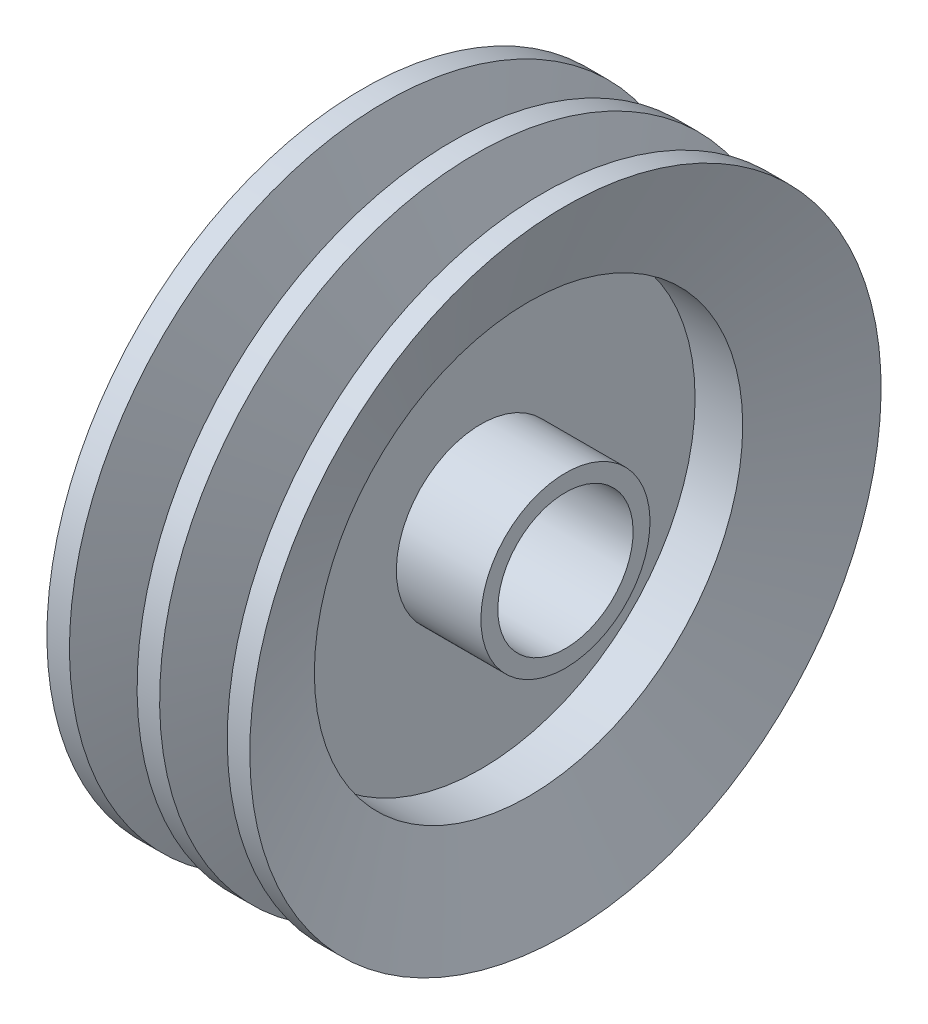
SolidWorks part; units mm, degrees
ref_plane "Alzado" through (0, 0, 0) normal (0, 0, 1) x (1, 0, 0)
ref_plane "Planta" through (0, 0, 0) normal (0, 1, 0) x (1, 0, 0)
ref_plane "Vista lateral" through (0, 0, 0) normal (1, 0, 0) x (0, 0, -1)
sketch "Croquis1" plane through (0, 0, 0) normal (0, 0, 1) x (1, 0, 0)
  line L0 (-45, 0) -> (45, 0) construction
  line L1 (-45, 30) -> (45, 30)
  line L2 (0, 30) -> (0, 140) construction
  line L3 (-5, 140) -> (5, 140)
  line L4 (5, 140) -> (15.9191, 110)
  line L5 (15.9191, 110) -> (24.0809, 110)
  line L6 (24.0809, 110) -> (35, 140)
  line L7 (35, 140) -> (45, 140)
  line L8 (45, 140) -> (28.6213, 95)
  line L9 (28.6213, 95) -> (7.5, 95)
  line L10 (7.5, 95) -> (7.5, 37.5)
  line L11 (7.5, 37.5) -> (45, 37.5)
  line L12 (45, 37.5) -> (45, 30)
  line L13 (-45, 37.5) -> (-45, 30)
  line L14 (-7.5, 37.5) -> (-45, 37.5)
  line L15 (-7.5, 95) -> (-7.5, 37.5)
  line L16 (-28.6213, 95) -> (-7.5, 95)
  line L17 (-45, 140) -> (-28.6213, 95)
  line L18 (-35, 140) -> (-45, 140)
  line L19 (-24.0809, 110) -> (-35, 140)
  line L20 (-15.9191, 110) -> (-24.0809, 110)
  line L21 (-5, 140) -> (-15.9191, 110)
  point P3 (0, 0)
  point P26 (0, 0)
  point P27 (23.5731, 57.0822)
  point P28 (13.471, 110)
  point P29 (31.3763, 95)
  point P30 (14.2787, 110)
  point P31 (0, 0)
  point P32 (0, 0)
  point P33 (0, 0)
  dimension "D1" = 90
  dimension "D2" = 90
  dimension "D3" = 30
  dimension "D4" = 10
  dimension "D5" = 30
  dimension "D6" = 40
  dimension "D7" = 15
  dimension "D8" = 60
  dimension "D9" = 75
  dimension "D10" = 190
  dimension "D11" = 280
revolve "Revolución1" add sketch "Croquis1" angle 360 about L0
